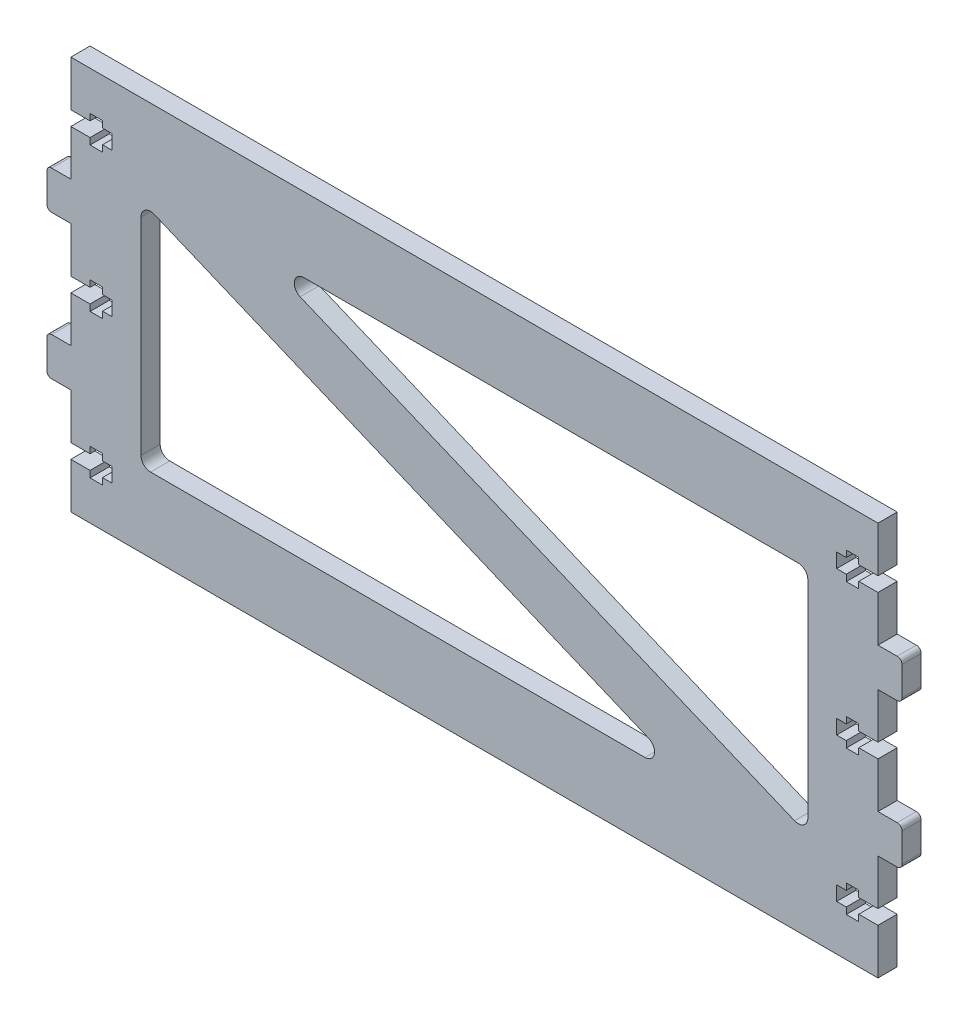
SolidWorks part; units mm, degrees
ref_plane "前视基准面" through (0, 0, 0) normal (0, 0, 1) x (1, 0, 0)
ref_plane "上视基准面" through (0, 0, 0) normal (0, 1, 0) x (1, 0, 0)
ref_plane "右视基准面" through (0, 0, 0) normal (1, 0, 0) x (0, 0, -1)
sketch "草图1" plane through (0, 0, 0) normal (0, 0, 1) x (1, 0, 0)
  line L0 (76.5343, 5.23) -> (-91.4657, 5.23) construction
  line L1 (80.5343, 20.23) -> (78.8313, 20.23) construction
  line L2 (46.9343, -24.77) -> (49.8557, -24.77) construction
  line L3 (59.5343, -9.77) -> (57.8313, -9.77) construction
  line L4 (76.5343, 3.73) -> (76.5343, 6.73) construction
  line L5 (76.5343, 5.23) -> (77.8421, 5.23) construction
  line L6 (76.5343, 6.73) -> (72.5343, 6.73)
  line L7 (72.5343, 6.73) -> (72.5343, 8.08)
  line L8 (72.5343, 8.08) -> (69.9343, 8.08)
  line L9 (69.9343, 8.08) -> (69.9343, 6.73)
  line L10 (69.9343, 6.73) -> (67.9343, 6.73)
  line L11 (69.9343, 2.38) -> (69.9343, 3.73)
  line L12 (72.5343, 3.73) -> (72.5343, 2.38)
  line L13 (69.9343, 3.73) -> (67.9343, 3.73)
  line L14 (72.5343, 2.38) -> (69.9343, 2.38)
  line L15 (76.5343, 3.73) -> (72.5343, 3.73)
  line L16 (76.5343, 24.23) -> (81.5343, 24.23)
  line L17 (81.5343, 24.23) -> (81.5343, 16.23)
  line L18 (81.5343, 16.23) -> (76.5343, 16.23)
  line L19 (76.5343, 16.23) -> (76.5343, 6.73)
  line L20 (-7.4657, 5.23) -> (-7.4657, 11.8034) construction
  line L21 (76.5343, 6.73) -> (72.5343, 6.73)
  line L22 (72.5343, 8.08) -> (69.9343, 8.08)
  line L23 (76.5343, 6.73) -> (72.5343, 6.73)
  line L24 (72.5343, 6.73) -> (72.5343, 8.08)
  line L25 (72.5343, 8.08) -> (69.9343, 8.08)
  line L26 (69.9343, 8.08) -> (69.9343, 6.73)
  line L27 (69.9343, 6.73) -> (67.9343, 6.73)
  line L28 (69.9343, 2.38) -> (69.9343, 3.73)
  line L29 (72.5343, 3.73) -> (72.5343, 2.38)
  line L30 (69.9343, 3.73) -> (67.9343, 3.73)
  line L31 (72.5343, 2.38) -> (69.9343, 2.38)
  line L32 (76.5343, 3.73) -> (72.5343, 3.73)
  line L33 (69.9343, 6.73) -> (67.9343, 6.73)
  line L34 (72.5343, 6.73) -> (72.5343, 8.08)
  line L35 (69.9343, 8.08) -> (69.9343, 6.73)
  line L36 (69.9343, 3.73) -> (67.9343, 3.73)
  line L37 (69.9343, 2.38) -> (69.9343, 3.73)
  line L38 (72.5343, 2.38) -> (69.9343, 2.38)
  line L39 (72.5343, 3.73) -> (72.5343, 2.38)
  line L40 (76.5343, 3.73) -> (72.5343, 3.73)
  line L41 (76.5343, -23.27) -> (76.5343, -13.77)
  line L42 (72.5343, -23.27) -> (76.5343, -23.27)
  line L43 (72.5343, -26.27) -> (76.5343, -26.27)
  line L44 (76.5343, -35.77) -> (76.5343, -26.27)
  line L45 (72.5343, -23.27) -> (72.5343, -21.92)
  line L46 (72.5343, -21.92) -> (69.9343, -21.92)
  line L47 (69.9343, -21.92) -> (69.9343, -23.27)
  line L48 (69.9343, -23.27) -> (67.9343, -23.27)
  line L49 (67.9343, -23.27) -> (67.9343, -26.27)
  line L50 (69.9343, -27.62) -> (69.9343, -26.27)
  line L51 (72.5343, -26.27) -> (72.5343, -27.62)
  line L52 (69.9343, -26.27) -> (67.9343, -26.27)
  line L53 (72.5343, -27.62) -> (69.9343, -27.62)
  line L54 (76.5343, -5.77) -> (76.5343, 3.73)
  line L55 (81.5343, -5.77) -> (76.5343, -5.77)
  line L56 (81.5343, -13.77) -> (81.5343, -5.77)
  line L57 (76.5343, -13.77) -> (81.5343, -13.77)
  line L58 (76.5343, 6.73) -> (72.5343, 6.73)
  line L59 (72.5343, 8.08) -> (69.9343, 8.08)
  line L60 (69.9343, 6.73) -> (67.9343, 6.73)
  line L61 (72.5343, 6.73) -> (72.5343, 8.08)
  line L62 (69.9343, 8.08) -> (69.9343, 6.73)
  line L63 (67.9343, 3.73) -> (67.9343, 6.73)
  line L64 (69.9343, 3.73) -> (67.9343, 3.73)
  line L65 (69.9343, 2.38) -> (69.9343, 3.73)
  line L66 (72.5343, 2.38) -> (69.9343, 2.38)
  line L67 (72.5343, 3.73) -> (72.5343, 2.38)
  line L68 (76.5343, 3.73) -> (72.5343, 3.73)
  line L69 (46.9343, 35.23) -> (49.8557, 35.23) construction
  line L70 (72.5343, 38.08) -> (69.9343, 38.08)
  line L71 (69.9343, 36.73) -> (67.9343, 36.73)
  line L72 (72.5343, 36.73) -> (72.5343, 38.08)
  line L73 (69.9343, 38.08) -> (69.9343, 36.73)
  line L74 (67.9343, 33.73) -> (67.9343, 36.73)
  line L75 (69.9343, 33.73) -> (67.9343, 33.73)
  line L76 (69.9343, 32.38) -> (69.9343, 33.73)
  line L77 (72.5343, 32.38) -> (69.9343, 32.38)
  line L78 (72.5343, 33.73) -> (72.5343, 32.38)
  line L79 (76.5343, 46.23) -> (76.5343, 36.73)
  line L80 (72.5343, 36.73) -> (76.5343, 36.73)
  line L81 (72.5343, 33.73) -> (76.5343, 33.73)
  line L82 (76.5343, 33.73) -> (76.5343, 24.23)
  line L83 (-61.8657, 35.23) -> (-64.7872, 35.23) construction
  line L84 (-91.4657, 5.23) -> (-92.7735, 5.23) construction
  line L85 (-91.4657, 3.73) -> (-91.4657, 6.73) construction
  line L86 (-74.4657, -9.77) -> (-72.7628, -9.77) construction
  line L87 (-61.8657, -24.77) -> (-64.7872, -24.77) construction
  line L88 (-95.4657, 20.23) -> (-93.7628, 20.23) construction
  line L89 (-91.4657, 33.73) -> (-91.4657, 24.23)
  line L90 (-87.4657, 33.73) -> (-91.4657, 33.73)
  line L91 (-87.4657, 36.73) -> (-91.4657, 36.73)
  line L92 (-91.4657, 46.23) -> (-91.4657, 36.73)
  line L93 (-87.4657, 33.73) -> (-87.4657, 32.38)
  line L94 (-87.4657, 32.38) -> (-84.8657, 32.38)
  line L95 (-84.8657, 32.38) -> (-84.8657, 33.73)
  line L96 (-84.8657, 33.73) -> (-82.8657, 33.73)
  line L97 (-82.8657, 33.73) -> (-82.8657, 36.73)
  line L98 (-84.8657, 38.08) -> (-84.8657, 36.73)
  line L99 (-87.4657, 36.73) -> (-87.4657, 38.08)
  line L100 (-84.8657, 36.73) -> (-82.8657, 36.73)
  line L101 (-87.4657, 38.08) -> (-84.8657, 38.08)
  line L102 (-91.4657, 3.73) -> (-87.4657, 3.73)
  line L103 (-87.4657, 3.73) -> (-87.4657, 2.38)
  line L104 (-87.4657, 2.38) -> (-84.8657, 2.38)
  line L105 (-84.8657, 2.38) -> (-84.8657, 3.73)
  line L106 (-84.8657, 3.73) -> (-82.8657, 3.73)
  line L107 (-82.8657, 3.73) -> (-82.8657, 6.73)
  line L108 (-84.8657, 8.08) -> (-84.8657, 6.73)
  line L109 (-87.4657, 6.73) -> (-87.4657, 8.08)
  line L110 (-84.8657, 6.73) -> (-82.8657, 6.73)
  line L111 (-87.4657, 8.08) -> (-84.8657, 8.08)
  line L112 (-91.4657, 6.73) -> (-87.4657, 6.73)
  line L113 (-91.4657, -13.77) -> (-96.4657, -13.77)
  line L114 (-96.4657, -13.77) -> (-96.4657, -5.77)
  line L115 (-96.4657, -5.77) -> (-91.4657, -5.77)
  line L116 (-91.4657, -5.77) -> (-91.4657, 3.73)
  line L117 (-87.4657, -27.62) -> (-84.8657, -27.62)
  line L118 (-84.8657, -26.27) -> (-82.8657, -26.27)
  line L119 (-87.4657, -26.27) -> (-87.4657, -27.62)
  line L120 (-84.8657, -27.62) -> (-84.8657, -26.27)
  line L121 (-82.8657, -23.27) -> (-82.8657, -26.27)
  line L122 (-84.8657, -23.27) -> (-82.8657, -23.27)
  line L123 (-84.8657, -21.92) -> (-84.8657, -23.27)
  line L124 (-87.4657, -21.92) -> (-84.8657, -21.92)
  line L125 (-87.4657, -23.27) -> (-87.4657, -21.92)
  line L126 (-91.4657, -35.77) -> (-91.4657, -26.27)
  line L127 (-87.4657, -26.27) -> (-91.4657, -26.27)
  line L128 (-87.4657, -23.27) -> (-91.4657, -23.27)
  line L129 (-91.4657, -23.27) -> (-91.4657, -13.77)
  line L130 (-91.4657, 3.73) -> (-87.4657, 3.73)
  line L131 (-87.4657, 3.73) -> (-87.4657, 2.38)
  line L132 (-87.4657, 2.38) -> (-84.8657, 2.38)
  line L133 (-84.8657, 2.38) -> (-84.8657, 3.73)
  line L134 (-84.8657, 3.73) -> (-82.8657, 3.73)
  line L135 (-84.8657, 8.08) -> (-84.8657, 6.73)
  line L136 (-87.4657, 6.73) -> (-87.4657, 8.08)
  line L137 (-84.8657, 6.73) -> (-82.8657, 6.73)
  line L138 (-91.4657, 3.73) -> (-87.4657, 3.73)
  line L139 (-87.4657, 2.38) -> (-84.8657, 2.38)
  line L140 (-84.8657, 3.73) -> (-82.8657, 3.73)
  line L141 (-87.4657, 3.73) -> (-87.4657, 2.38)
  line L142 (-84.8657, 2.38) -> (-84.8657, 3.73)
  line L143 (-84.8657, 6.73) -> (-82.8657, 6.73)
  line L144 (-84.8657, 8.08) -> (-84.8657, 6.73)
  line L145 (-87.4657, 8.08) -> (-84.8657, 8.08)
  line L146 (-87.4657, 6.73) -> (-87.4657, 8.08)
  line L147 (-91.4657, 6.73) -> (-87.4657, 6.73)
  line L148 (-87.4657, 8.08) -> (-84.8657, 8.08)
  line L149 (-91.4657, 6.73) -> (-87.4657, 6.73)
  line L150 (-91.4657, 16.23) -> (-91.4657, 6.73)
  line L151 (-96.4657, 16.23) -> (-91.4657, 16.23)
  line L152 (-96.4657, 24.23) -> (-96.4657, 16.23)
  line L153 (-91.4657, 24.23) -> (-96.4657, 24.23)
  line L154 (-91.4657, 3.73) -> (-87.4657, 3.73)
  line L155 (-87.4657, 2.38) -> (-84.8657, 2.38)
  line L156 (-84.8657, 3.73) -> (-82.8657, 3.73)
  line L157 (-87.4657, 3.73) -> (-87.4657, 2.38)
  line L158 (-84.8657, 2.38) -> (-84.8657, 3.73)
  line L159 (-84.8657, 6.73) -> (-82.8657, 6.73)
  line L160 (-84.8657, 8.08) -> (-84.8657, 6.73)
  line L161 (-87.4657, 8.08) -> (-84.8657, 8.08)
  line L162 (-87.4657, 6.73) -> (-87.4657, 8.08)
  line L163 (-91.4657, 6.73) -> (-87.4657, 6.73)
  line L164 (-91.4657, 46.23) -> (54.5343, 46.23)
  line L165 (54.5343, -35.77) -> (-91.4657, -35.77)
  line L166 (54.5343, 46.23) -> (76.5343, 46.23)
  line L167 (76.5343, -35.77) -> (54.5343, -35.77)
  dimension "D1" = 3
  dimension "D2" = 15
  dimension "D3" = 84
extrude "凸台-拉伸1" add sketch "草图1" along normal blind 4
sketch "草图2" plane through (76.5343, 0, 0) normal (1, 0, 0) x (0, 0, -1)
  line L0 (-2, -26.27) -> (-2, -23.27)
  line L1 (-4, -26.27) -> (0, -26.27) construction
  line L2 (-4, -23.27) -> (0, -23.27) construction
  circle A0 centre (-2, -24.77) radius 1.5
sketch "草图3" plane through (0, 0, 4) normal (0, 0, 1) x (1, 0, 0)
  line L23 (-82.8657, 36.73) -> (-82.8657, -26.27) construction
  line L24 (-82.8657, -26.27) -> (67.9343, -26.27) construction
  line L26 (67.9343, -26.27) -> (-82.8657, 36.73) construction
  line L33 (28.8029, -16.4246) -> (-74.0947, 26.5632)
  line L34 (-76.8657, 24.7178) -> (-76.8657, -18.27)
  line L35 (-74.8657, -20.27) -> (28.032, -20.27)
  line L36 (-82.8657, 36.73) -> (67.9343, 36.73) construction
  line L37 (67.9343, 36.73) -> (67.9343, -26.27) construction
  line L38 (-42.9634, 30.73) -> (59.9343, 30.73)
  line L39 (61.9343, 28.73) -> (61.9343, -14.2578)
  line L40 (59.1633, -16.1032) -> (-43.7344, 26.8846)
  line L41 (61.9343, 30.73) -> (61.9343, -17.2608) construction
  line L42 (-52.939, 30.73) -> (61.9343, 30.73) construction
  line L43 (61.9343, -17.2608) -> (-52.939, 30.73) construction
  line L44 (38.0075, -20.27) -> (-76.8657, 27.7208) construction
  line L45 (-76.8657, -20.27) -> (38.0075, -20.27) construction
  line L46 (-76.8657, 27.7208) -> (-76.8657, -20.27) construction
  arc A0 (61.9343, 28.73) -> (59.9343, 30.73) centre (59.9343, 28.73) ccw
  arc A1 (61.9343, -14.2578) -> (59.1633, -16.1032) centre (59.9343, -14.2578) cw
  arc A2 (-42.9634, 30.73) -> (-43.7344, 26.8846) centre (-42.9634, 28.73) ccw
  arc A3 (28.8029, -16.4246) -> (28.032, -20.27) centre (28.032, -18.27) cw
  arc A4 (-74.8657, -20.27) -> (-76.8657, -18.27) centre (-74.8657, -18.27) cw
  arc A5 (-74.0947, 26.5632) -> (-76.8657, 24.7178) centre (-74.8657, 24.7178) ccw
  dimension "D1" = 6
  dimension "D3" = 2
  dimension "D2" = 6
extrude "切除-拉伸1" cut sketch "草图3" against normal blind 10
fillet "圆角1" radius 1 8 edges at (-96.4657, 24.23, 2) (-96.4657, 16.23, 2) (-96.4657, -5.77, 2) (-96.4657, -13.77, 2) (81.5343, -13.77, 2) (81.5343, -5.77, 2) (81.5343, 16.23, 2) (81.5343, 24.23, 2)
